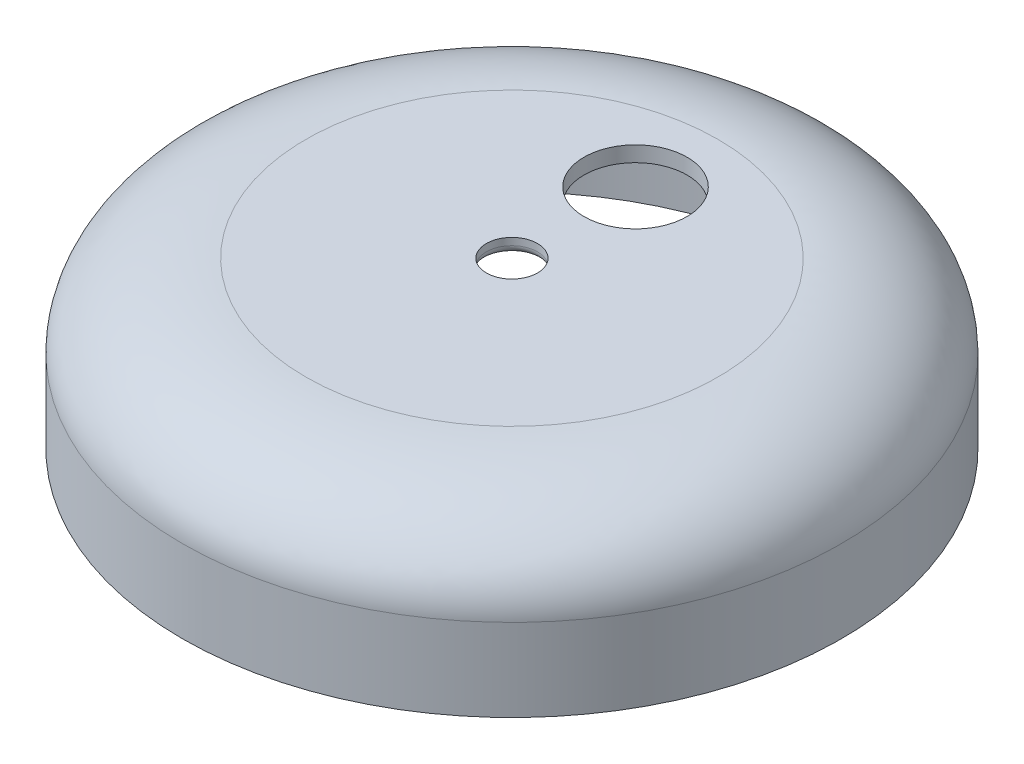
SolidWorks part; units mm, degrees
material "6061-T6 (SS)"
ref_plane "Front" through (0, 0, 0) normal (0, 0, 1) x (1, 0, 0)
ref_plane "Top" through (0, 0, 0) normal (0, 1, 0) x (1, 0, 0)
ref_plane "Right" through (0, 0, 0) normal (1, 0, 0) x (0, 0, -1)
sketch "Sketch1" plane through (0, 0, 0) normal (0, 0, 1) x (1, 0, 0)
  line L0 (0, 0) -> (101.6, 0) construction
  line L1 (101.6, 0) -> (101.6, -67.9188) construction
  line L2 (0, 29.5111) -> (0, -26.7187) construction
  line L3 (0, 0) -> (0, -4.7625)
  line L4 (0, 0) -> (63.5, 0)
  line L5 (0, -4.7625) -> (63.5, -4.7625)
  line L6 (101.6, 5.9654) -> (96.8375, 5.9654) construction
  line L7 (96.8375, 5.9654) -> (96.8375, -58.8285) construction
  line L9 (63.5, -25.4) -> (127.5739, -25.4) construction
  line L12 (63.5, 0) -> (63.5, -38.8167) construction
  line L14 (96.8375, -50.8) -> (101.6, -50.8)
  line L15 (101.6, -50.8) -> (101.6, -25.4)
  line L16 (96.8375, -50.8) -> (96.8375, -25.4)
  ellipse E0 centre (63.5, -25.4) end of major axis (96.8375, -25.4) minor radius 20.6375 (96.8375, -25.4) -> (63.5, -4.7625) ccw
  ellipse E1 centre (63.5, -25.4) end of major axis (25.4, -25.4) minor radius 25.4 (63.5, 0) -> (101.6, -25.4) cw
  dimension "D1" = 101.6
  dimension "D2" = 63.5
  dimension "D3" = 25.4
  dimension "D4" = 4.7625
  dimension "D5" = 4.7625
  dimension "D6" = 25.4
revolve "Revolve1" add sketch "Sketch1" angle 360 about L2
sketch "Sketch2" plane through (0, 0, 0) normal (0, 1, 0) x (1, 0, 0)
  line L0 (0, 0) -> (0, 199.7485) construction
  line L1 (0, 0) -> (303.3008, 0) construction
  circle A0 centre (0, 38.1) radius 15.875
  circle A1 centre (0, 0) radius 7.874
  dimension "D1" = 31.75
  dimension "D3" = 15.748
  dimension "D2" = 38.1
extrude "Cut-Extrude1" cut sketch "Sketch2" against normal blind 25.4
fillet "Fillet1" radius 2.54 1 edges at (0, -4.7625, 7.874)
